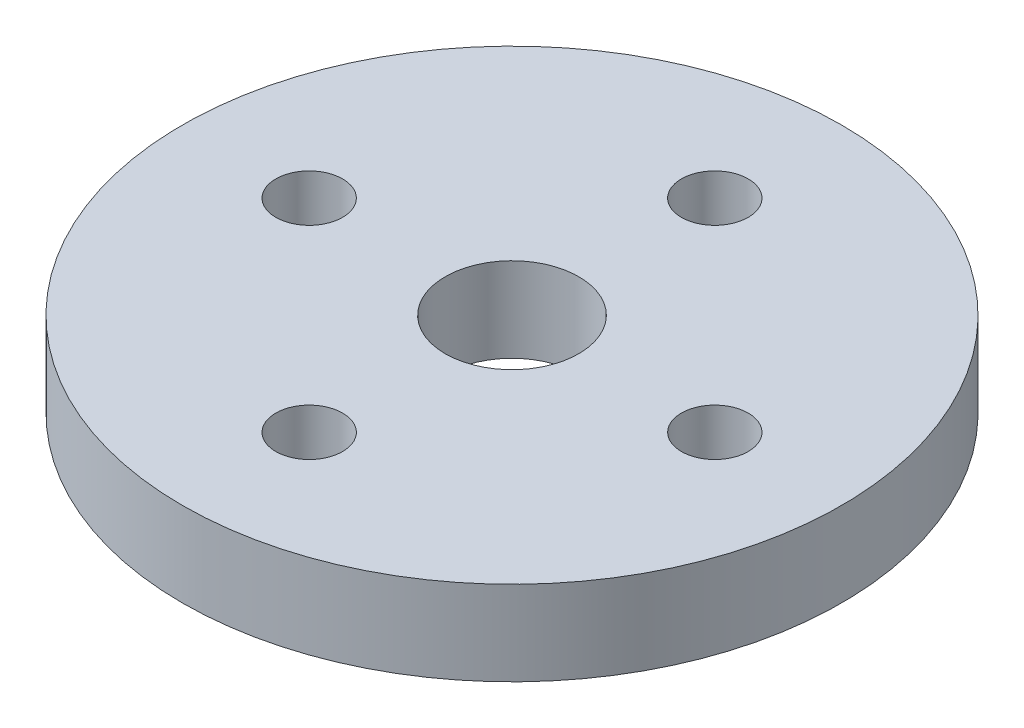
SolidWorks part; units mm, degrees
ref_plane "Front Plane" through (0, 0, 0) normal (0, 0, 1) x (1, 0, 0)
ref_plane "Top Plane" through (0, 0, 0) normal (0, 1, 0) x (1, 0, 0)
ref_plane "Right Plane" through (0, 0, 0) normal (1, 0, 0) x (0, 0, -1)
sketch "Sketch1" plane through (0, 0, 0) normal (0, 1, 0) x (1, 0, 0)
  line L0 (0, 19.5) -> (0, -19.5) construction
  line L1 (-19.5, 0) -> (19.5, 0) construction
  circle A0 centre (0, 0) radius 19.5
  circle A1 centre (0, 0) radius 3.95
  circle A2 centre (0, 12) radius 1.975
  circle A3 centre (-12, 0) radius 1.975
  circle A4 centre (12, 0) radius 1.975
  circle A5 centre (0, -12) radius 1.975
  dimension "D1" = 39
  dimension "D2" = 7.9
  dimension "D4" = 3.95
  dimension "D3" = 12
  dimension "D5" = 12
extrude "Boss-Extrude1" add sketch "Sketch1" along normal blind 5
